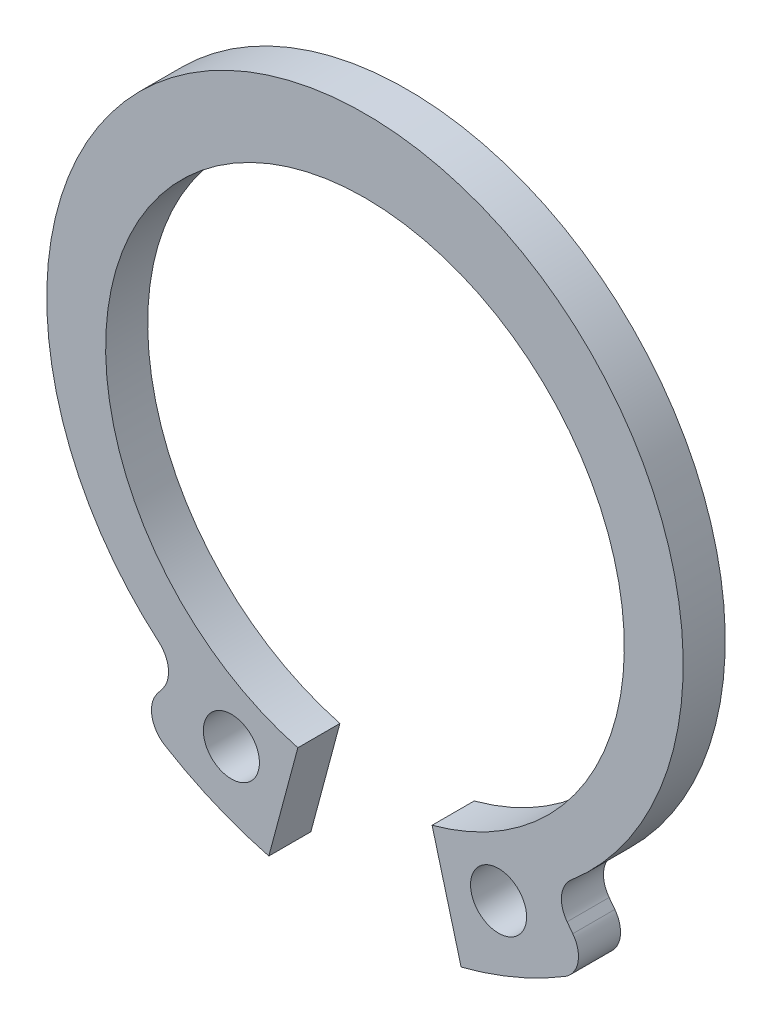
SolidWorks part; units mm, degrees
ref_plane "Plan1" through (0, 0, 0) normal (0, 0, 1) x (1, 0, 0)
ref_plane "Plan2" through (0, 0, 0) normal (0, 1, 0) x (1, 0, 0)
ref_plane "Plan3" through (0, 0, 0) normal (1, 0, 0) x (0, 0, -1)
sketch "Esquisse1" plane through (0, 0, 0) normal (0, 0, 1) x (1, 0, 0)
  line L0 (0, 0) -> (3.4294, -12.7985) construction
  line L1 (0, 0) -> (0, -67.082) construction
  line L2 (7.209, -9.5078) -> (7.4124, -9.776)
  line L3 (2.3941, -8.9348) -> (3.4294, -12.7985)
  line L4 (-2.3941, -8.9348) -> (-3.4294, -12.7985)
  line L5 (-7.209, -9.5078) -> (-7.4124, -9.776)
  line L6 (2.3941, -8.9348) -> (7.1351, -11.2346) construction
  line L7 (0, 0) -> (0, 9.25) construction
  line L8 (0, 9.25) -> (0, 11.85) construction
  arc A0 (2.3941, -8.9348) -> (-2.3941, -8.9348) centre (0, 0) ccw
  arc A1 (3.4294, -12.7985) -> (7.1351, -11.2346) centre (0, 0.5) ccw
  arc A2 (7.3576, -8.1422) -> (-7.3576, -8.1422) centre (0, 0.5) ccw
  arc A3 (-7.1351, -11.2346) -> (-3.4294, -12.7985) centre (0, 0.5) ccw
  arc A4 (-7.3576, -8.1422) -> (-7.209, -9.5078) centre (-8.0059, -8.9036) cw
  arc A5 (7.3576, -8.1422) -> (7.209, -9.5078) centre (8.0059, -8.9036) ccw
  circle A6 centre (4.7646, -10.0847) radius 1
  circle A7 centre (-4.7646, -10.0847) radius 1
  arc A8 (-7.1351, -11.2346) -> (-7.4124, -9.776) centre (-6.6155, -10.3802) cw
  arc A9 (7.1351, -11.2346) -> (7.4124, -9.776) centre (6.6155, -10.3802) ccw
  point P22 (-8.0549, -10.6234)
  dimension "D1" = 18.5
  dimension "D2" = 4
  dimension "D3" = 2.6
  dimension "D8" = 2
  dimension "D4" = 0.5
  dimension "D5" = 5
  dimension "a" = 15
extrude "Base-Extrusion" add sketch "Esquisse1" along normal blind 1.5
equation "\"R@Esquisse1\" = \"D8@Esquisse1\"/2"
equation "\"D4@Esquisse1\"=\"R@Esquisse1\"/2"
equation "\"D5@Esquisse1\"=\"D8@Esquisse1\"*2.5"
